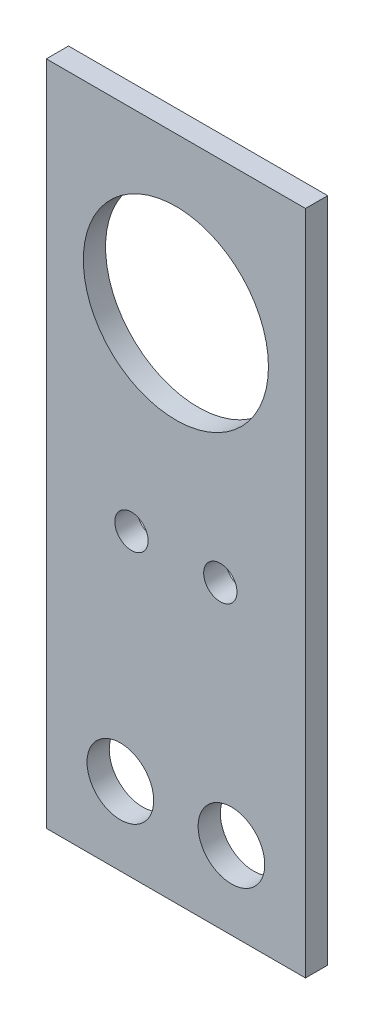
SolidWorks part; units mm, degrees
ref_plane "Front Plane" through (0, 0, 0) normal (0, 0, 1) x (1, 0, 0)
ref_plane "Top Plane" through (0, 0, 0) normal (0, 1, 0) x (1, 0, 0)
ref_plane "Right Plane" through (0, 0, 0) normal (1, 0, 0) x (0, 0, -1)
sketch "Sketch1" plane through (0, 13.434, 0) normal (0, 1, 0) x (1, 0, 0)
  line L0 (-201.526, 170.5) -> (298.474, 170.5) construction
  line L1 (-1.526, 173.5) -> (-36.526, 173.5)
  line L2 (-1.526, 173.5) -> (-1.526, 170.5)
  line L3 (-1.526, 170.5) -> (-36.526, 170.5)
  line L4 (-36.526, 173.5) -> (-36.526, 170.5)
  line L6 (-31.526, 183.55) -> (-31.526, 108.55) construction
  line L7 (-6.526, 108.55) -> (-6.526, 183.55) construction
  dimension "D1" = 5
  dimension "D2" = 5
  dimension "D3" = 3
extrude "Boss-Extrude1" add sketch "Sketch1" along normal blind 10 and the other way blind 80
sketch "Sketch2" plane through (0, 0, -170.5) normal (0, 0, 1) x (1, 0, 0)
  circle A0 centre (-19.026, 2.434) radius 12.5
  dimension "D1" = 25
extrude "25mm thru" cut sketch "Sketch2" against normal through all
sketch "Sketch3" plane through (0, 0, -170.5) normal (0, 0, 1) x (1, 0, 0)
  line L0 (-1.526, -66.566) -> (-36.526, -66.566) construction
  line L3 (-25.026, -26.066) -> (-13.026, -26.066) construction
  circle A0 centre (-25.026, -26.066) radius 2.25
  circle A1 centre (-13.026, -26.066) radius 2.25
  dimension "D1" = 4.5
  dimension "D2" = 4.5
  dimension "D3" = 40.5
extrude "M4 clearance - 4.5 -thru" cut sketch "Sketch3" against normal through all
sketch "Sketch4" plane through (0, 0, -173.5) normal (0, 0, -1) x (-1, 0, 0)
  line L0 (1.526, -66.566) -> (36.526, -66.566) construction
  line L3 (2.315, -56.066) -> (29.6811, -56.066) construction
  line L4 (1.526, -66.566) -> (1.526, 23.434) construction
  circle A0 centre (11.526, -56.066) radius 4.5
  circle A1 centre (26.526, -56.066) radius 4.5
  point P6 (-0.7127, -56.066)
  dimension "D1" = 9
  dimension "D2" = 9
  dimension "D3" = 15
  dimension "D4" = 10
  dimension "D5" = 10.5
extrude "M8 clearance - 9mm thru" cut sketch "Sketch4" against normal through all
